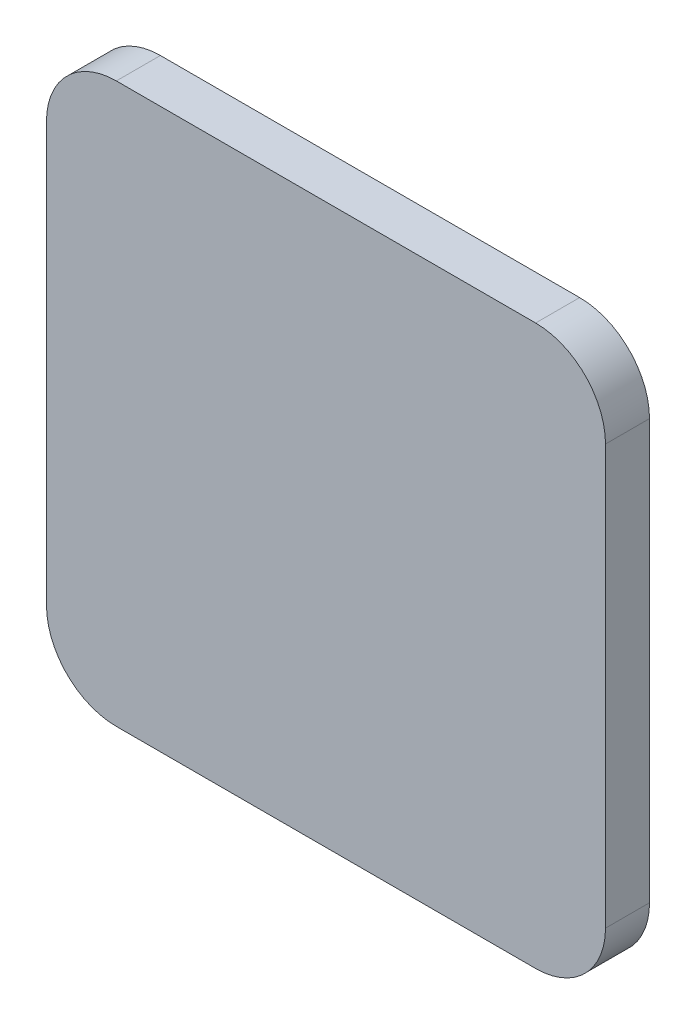
SolidWorks part; units mm, degrees
ref_plane "1" through (0, 0, 0) normal (0, 0, 1) x (1, 0, 0)
ref_plane "2" through (0, 0, 0) normal (0, 1, 0) x (1, 0, 0)
ref_plane "3" through (0, 0, 0) normal (1, 0, 0) x (0, 0, -1)
ref_plane "Front Plane" through (0, 0, 0) normal (0, -1, 0) x (1, 0, 0)
ref_plane "Right Plane" through (0, 0, 0) normal (1, 0, 0) x (0, 1, 0)
ref_plane "Top Plane" through (0, 0, 0) normal (0, 0, 1) x (1, 0, 0)
ref_plane "Plane1" through (0, 0, 2.3) normal (0, 0, 1) x (1, 0, 0)
sketch "Sketch1" plane through (0, 0, 0) normal (0, 0, 1) x (1, 0, 0)
  line L0 (-10.16, 10.16) -> (10.16, 10.16) construction
  line L1 (-10.16, 10.16) -> (-10.16, -10.16) construction
  line L2 (10.16, 10.16) -> (10.16, -10.16) construction
  line L3 (-10.16, -10.16) -> (10.16, -10.16) construction
  line L4 (0, 10.16) -> (0, 15.7652) construction
  line L5 (10.16, 0) -> (24.8253, 0) construction
  dimension "D1" = 20.32
  dimension "D2" = 20.32
sketch "Sketch2" plane through (0, 0, 2.3) normal (0, 0, 1) x (1, 0, 0)
  line L0 (-7.62, 10.16) -> (7.62, 10.16)
  line L1 (-10.16, 7.62) -> (-10.16, -7.62)
  line L2 (10.16, 7.62) -> (10.16, -7.62)
  line L3 (-7.62, -10.16) -> (7.62, -10.16)
  line L4 (-10.16, 10.16) -> (10.16, 10.16) construction
  line L5 (-10.16, 10.16) -> (-10.16, -10.16) construction
  line L6 (-10.16, -10.16) -> (10.16, -10.16) construction
  line L7 (10.16, 10.16) -> (10.16, -10.16) construction
  arc A0 (10.16, -7.62) -> (7.62, -10.16) centre (7.62, -7.62) cw
  arc A1 (-10.16, -7.62) -> (-7.62, -10.16) centre (-7.62, -7.62) ccw
  arc A2 (-10.16, 7.62) -> (-7.62, 10.16) centre (-7.62, 7.62) cw
  arc A3 (7.62, 10.16) -> (10.16, 7.62) centre (7.62, 7.62) cw
  dimension "D1" = 2.54
extrude "Boss-Extrude1" add sketch "Sketch2" along normal blind 1.6
